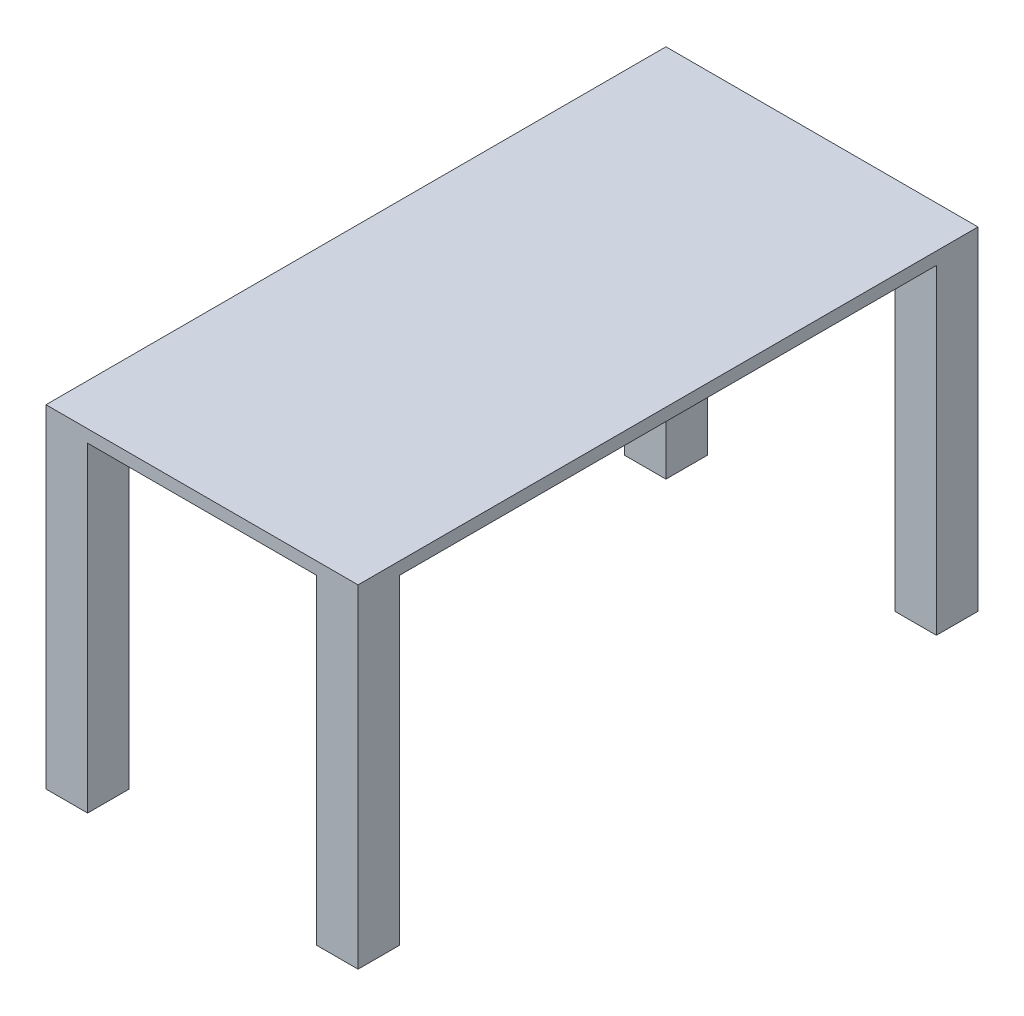
SolidWorks part; units mm, degrees
ref_plane "Front Plane" through (0, 0, 0) normal (0, 0, 1) x (1, 0, 0)
ref_plane "Top Plane" through (0, 0, 0) normal (0, 1, 0) x (1, 0, 0)
ref_plane "Right Plane" through (0, 0, 0) normal (1, 0, 0) x (0, 0, -1)
sketch "Sketch1" plane through (0, 0, 0) normal (0, 1, 0) x (1, 0, 0)
  line L1 (0, 0) -> (750, 0)
  line L2 (0, 0) -> (0, 1490)
  line L3 (0, 1490) -> (750, 1490)
  line L4 (750, 0) -> (750, 1490)
  dimension "D1" = 750
  dimension "D2" = 1490
extrude "Boss-Extrude1" add sketch "Sketch1" along normal blind 30
sketch "Sketch2" plane through (0, 30, 0) normal (0, 1, 0) x (1, 0, 0)
  line L0 (375, 0) -> (375, 1544.3373) construction
  line L1 (0, 0) -> (100, 0)
  line L2 (0, 0) -> (0, 100)
  line L3 (0, 100) -> (100, 100)
  line L4 (100, 0) -> (100, 100)
  line L5 (0, 0) -> (750, 0) construction
  line L6 (750, 0) -> (750, 100)
  line L7 (750, 0) -> (650, 0)
  line L8 (650, 0) -> (650, 100)
  line L9 (750, 100) -> (650, 100)
  line L10 (0, 745) -> (933.2854, 745) construction
  line L11 (0, 1490) -> (0, 0) construction
  line L12 (750, 1390) -> (650, 1390)
  line L13 (650, 1490) -> (650, 1390)
  line L14 (750, 1490) -> (650, 1490)
  line L15 (750, 1490) -> (750, 1390)
  line L16 (100, 1490) -> (100, 1390)
  line L17 (0, 1390) -> (100, 1390)
  line L18 (0, 1490) -> (0, 1390)
  line L19 (0, 1490) -> (100, 1490)
  dimension "D1" = 100
  dimension "D2" = 100
extrude "Boss-Extrude2" add sketch "Sketch2" against normal blind 800
